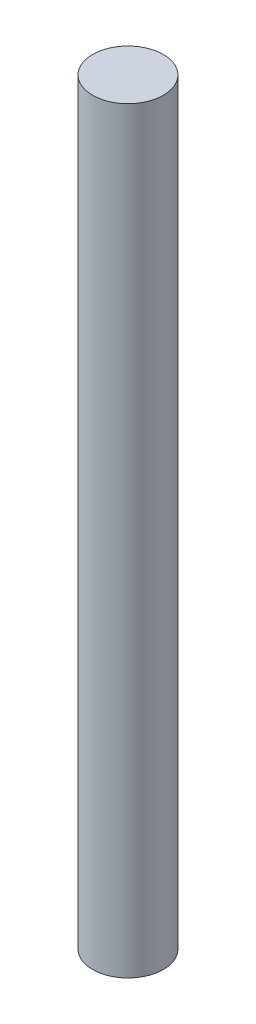
SolidWorks part; units mm, degrees
ref_plane "Front Plane" through (0, 0, 0) normal (0, 0, 1) x (1, 0, 0)
ref_plane "Top Plane" through (0, 0, 0) normal (0, 1, 0) x (1, 0, 0)
ref_plane "Right Plane" through (0, 0, 0) normal (1, 0, 0) x (0, 0, -1)
sketch "Sketch1" plane through (0, 0, 0) normal (0, 1, 0) x (1, 0, 0)
  circle A0 centre (0, 0) radius 1.5875
  dimension "D1" = 3.175
extrude "Boss-Extrude1" add sketch "Sketch1" along normal blind 34
